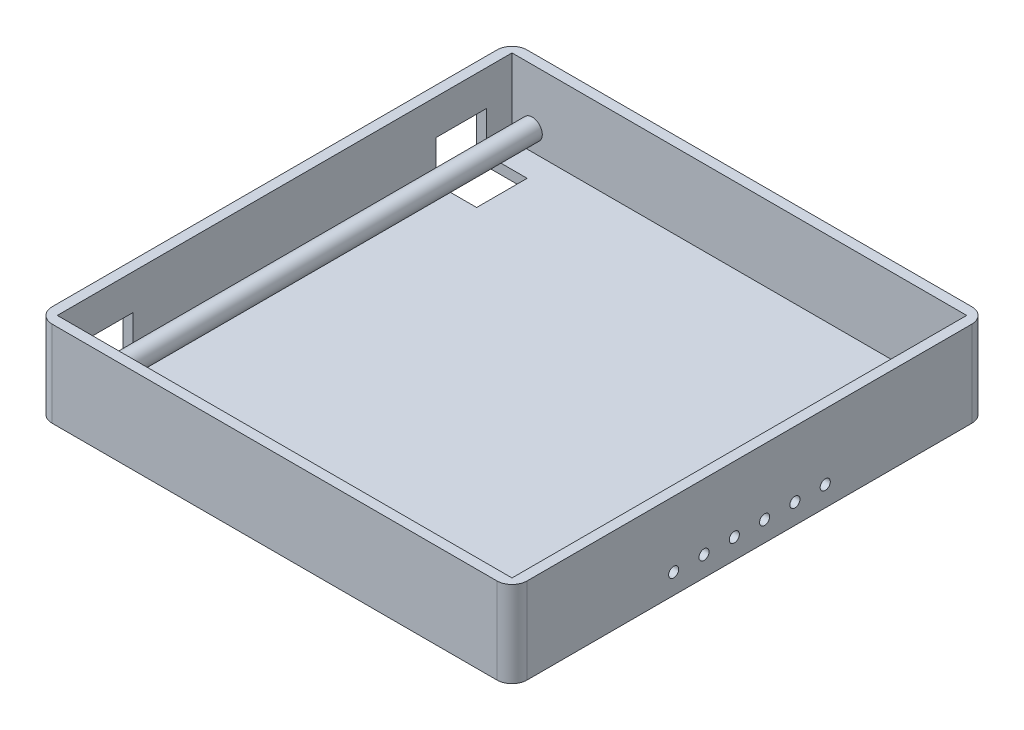
SolidWorks part; units mm, degrees
ref_plane "Front Plane" through (0, 0, 0) normal (0, 0, 1) x (1, 0, 0)
ref_plane "Top Plane" through (0, 0, 0) normal (0, 1, 0) x (1, 0, 0)
ref_plane "Right Plane" through (0, 0, 0) normal (1, 0, 0) x (0, 0, -1)
sketch "Sketch1" plane through (0, 0, 0) normal (0, 1, 0) x (1, 0, 0)
  line L1 (0, 0) -> (47, 0)
  line L2 (0, 0) -> (0, 47)
  line L3 (0, 47) -> (47, 47)
  line L4 (47, 0) -> (47, 47)
  dimension "D1" = 47
  dimension "D2" = 47
extrude "Boss-Extrude1" add sketch "Sketch1" along normal blind 1
sketch "Sketch2" plane through (0, 1, 0) normal (0, 1, 0) x (1, 0, 0)
  line L8 (0, 47) -> (0, 0)
  line L9 (0, 0) -> (47, 0)
  line L10 (47, 0) -> (47, 47)
  line L11 (47, 47) -> (0, 47)
  line L12 (0, 47) -> (0, 0)
  line L13 (0, 0) -> (47, 0)
  line L14 (47, 0) -> (47, 47)
  line L15 (47, 47) -> (0, 47)
  line L20 (1, 46) -> (1, 1)
  line L21 (1, 1) -> (46, 1)
  line L22 (46, 1) -> (46, 46)
  line L23 (46, 46) -> (1, 46)
  line L24 (1, 46) -> (1, 1)
  line L25 (1, 1) -> (46, 1)
  line L26 (46, 1) -> (46, 46)
  line L27 (46, 46) -> (1, 46)
  dimension "D1" = 0
  dimension "D2" = 1
extrude "Boss-Extrude2" add sketch "Sketch2" along normal blind 7.5
sketch "Sketch4" plane through (47, 0, 0) normal (1, 0, 0) x (0, 0, -1)
  line L0 (0, 0) -> (47, 0) construction
  line L1 (0, 8.5) -> (0, 0) construction
  circle A0 centre (16, 2) radius 0.5
  dimension "D1" = 1
  dimension "D2" = 2
  dimension "D3" = 16
extrude "Cut-Extrude3" cut sketch "Sketch4" against normal blind 1
pattern_linear "LPattern1" count 6 spacing 3 along (0, 0, -1) of "Cut-Extrude3"
fillet "Fillet1" radius 1.5 4 edges at (47, 4.25, 0) (0, 4.25, 0) (47, 4.25, -47) (0, 4.25, -47)
ref_plane "Plane1" through (0, 4.25, 0) normal (0, -1, 0) x (-1, 0, 0)
sketch "Sketch8" plane through (0, 0, 0) normal (-1, 0, 0) x (0, 0, 1)
  line L0 (-43.5, 0) -> (-43.5, 5)
  line L1 (-45.5, 0) -> (-1.5, 0) construction
  line L2 (-38.5, 5) -> (-38.5, 0)
  line L3 (-38.5, 0) -> (-43.5, 0)
  line L4 (-8.5, 0) -> (-8.5, 5)
  line L5 (-3.5, 5) -> (-3.5, 0)
  line L6 (-3.5, 0) -> (-8.5, 0)
  line L7 (-43.5, 5) -> (-38.5, 5)
  line L8 (-8.5, 5) -> (-3.5, 5)
  line L9 (-45.5, 8.5) -> (-45.5, 0) construction
  line L10 (-1.5, 0) -> (-1.5, 8.5) construction
  dimension "D2" = 5
  dimension "D1" = 5
  dimension "D3" = 2
  dimension "D4" = 5
  dimension "D5" = 5
  dimension "D6" = 2
extrude "Cut-Extrude4" cut sketch "Sketch8" against normal blind 5
sketch "Sketch9" plane through (0, 0, -46) normal (0, 0, 1) x (1, 0, 0)
  line L0 (1, 8.5) -> (1, 1) construction
  line L1 (46, 1) -> (1, 1) construction
  circle A0 centre (3, 3) radius 1
  dimension "D1" = 2
  dimension "D2" = 2
  dimension "D3" = 2
extrude "Boss-Extrude3" add sketch "Sketch9" along normal through all
